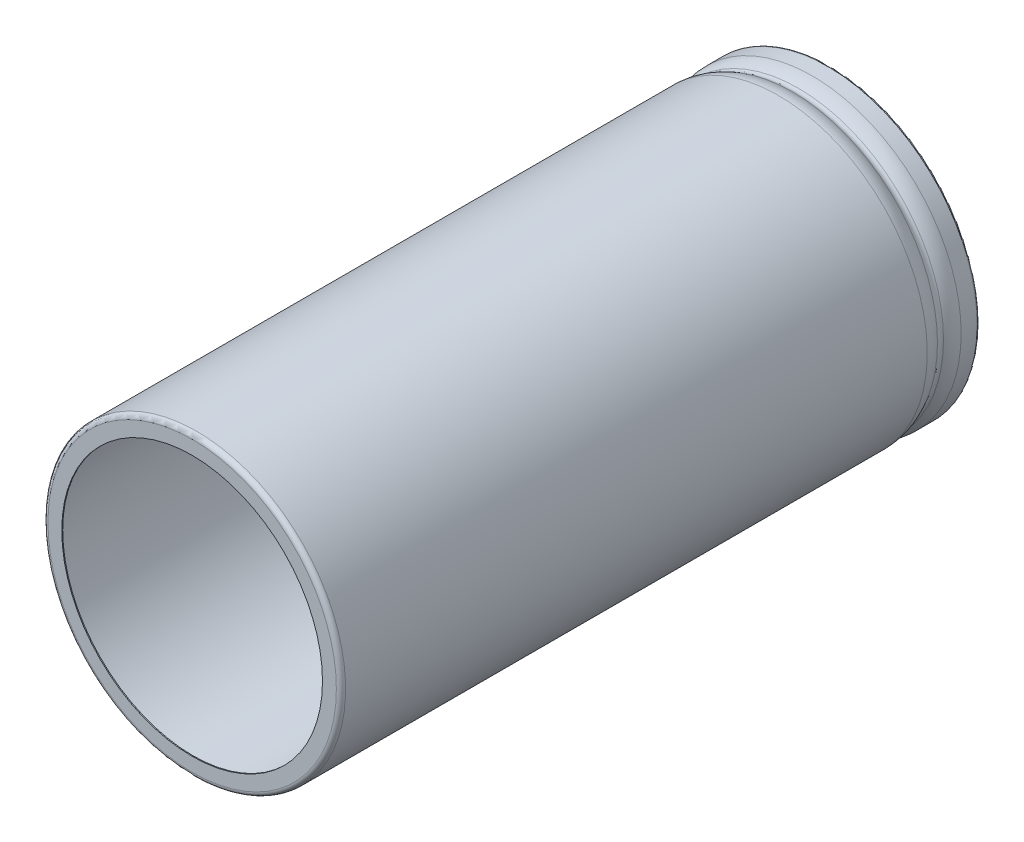
SolidWorks part; units mm, degrees
ref_plane "Front Plane" through (0, 0, 0) normal (0, 0, 1) x (1, 0, 0)
ref_plane "Top Plane" through (0, 0, 0) normal (0, 1, 0) x (1, 0, 0)
ref_plane "Right Plane" through (0, 0, 0) normal (1, 0, 0) x (0, 0, -1)
sketch "Sketch1" plane through (0, 0, 0) normal (1, 0, 0) x (0, 0, -1)
  line L0 (0, 16) -> (0, 13.1) construction
  line L1 (0, 0) -> (64.4, 0) construction
  line L2 (0, 0) -> (0, 16) construction
  line L3 (0, 16) -> (64.4, 16) construction
  line L4 (64.4, 0) -> (64.4, 16) construction
  line L5 (0, 13.1) -> (-0.6, 13.1) construction
  line L6 (-0.6, 13.1) -> (-0.6, 2.6) construction
  line L7 (0, 14.1) -> (-0.1, 14.1)
  line L8 (64.4, 14.2) -> (65.9, 14.2) construction
  line L9 (65.9, 14.2) -> (65.9, 16) construction
  line L10 (65.9, 16) -> (68.9, 16) construction
  line L11 (68.9, 16) -> (68.9, 11) construction
  line L12 (68.9, 11) -> (68.6, 11) construction
  line L13 (68.6, 11) -> (68.6, 15.7) construction
  line L14 (68.6, 15.7) -> (66.2, 15.7) construction
  line L15 (66.2, 15.7) -> (66.2, 13.9) construction
  line L16 (66.2, 13.9) -> (64.1, 13.9) construction
  line L17 (64.1, 13.9) -> (64.1, 15.7) construction
  line L18 (64.1, 15.7) -> (0.3, 15.7) construction
  line L19 (0.3, 15.7) -> (0.3, 12.8) construction
  line L20 (0.3, 12.8) -> (-0.3, 12.8) construction
  line L21 (-0.3, 12.8) -> (-0.3, 2.6) construction
  line L22 (64.4, 16) -> (64.4, 14.2) construction
  line L23 (-0.6, 2.6) -> (-0.3, 2.6) construction
  line L24 (-0.1, 14.1) -> (-0.1, 16.1)
  line L25 (-0.1, 16.1) -> (64.4, 16.1)
  line L26 (65.9, 16.1) -> (68.95, 16.1)
  line L27 (68.95, 16.1) -> (68.95, 13.1)
  line L28 (68.95, 13.1) -> (68.9, 13.1)
  line L29 (68.9, 13.1) -> (68.9, 16)
  line L30 (68.9, 16) -> (65.9, 16)
  line L31 (64.4, 16) -> (0, 16)
  line L32 (0, 16) -> (0, 14.1)
  line L33 (64.4, 15.55) -> (65.9, 15.55) construction
  line L34 (65.15, 15.5) -> (65.15, 15.6) construction
  spline S0 degree 2 poles (64.4, 16) (65.15, 15) (65.9, 16) knots 0 0 0 1 1 1
  spline S1 degree 2 poles (64.4, 16.1) (65.15, 15.1) (65.9, 16.1) knots 0 0 0 1 1 1
  point P25 (65.15, 15.55)
  point P29 (65.15, 15.55)
  dimension "D1" = 16
  dimension "D3" = 0.6
  dimension "D5" = 0.3
  dimension "D6" = 0.3
  dimension "D7" = 0.3
  dimension "D8" = 0.3
  dimension "D9" = 0.3
  dimension "D10" = 0.3
  dimension "D11" = 0.3
  dimension "D12" = 0.3
  dimension "D13" = 0.3
  dimension "D15" = 1.5
  dimension "D16" = 5
  dimension "D17" = 3
  dimension "D4" = 69.5
  dimension "D2" = 2.6
  dimension "D18" = 13.1
  dimension "D14" = 1.8
  dimension "D19" = 0.05
  dimension "D20" = 0.1
  dimension "D21" = 0.1
  dimension "D22" = 0.1
  dimension "D23" = 2
  dimension "D24" = 0.1
  dimension "D25" = 0.5
  dimension "D26" = 3
revolve "Revolve1" add sketch "Sketch1" angle 360 about L1
fillet "Fillet1" radius 0.25 2 edges at (16, 0, -68.9) (16.1, 0, -68.95)
fillet "Fillet2" radius 0.5 2 edges at (16, 0, 0) (16.1, 0, 0.1)
fillet "Fillet3" radius 3 4 edges at (16.1, 0, -65.9) (16.1, 0, -64.4) (16, 0, -65.9) (16, 0, -64.4)
equation "\"cellThickness\"=0.3"
equation "\"D13@Sketch1\"=\"cellThickness\""
equation "\"D12@Sketch1\"=\"cellThickness\""
